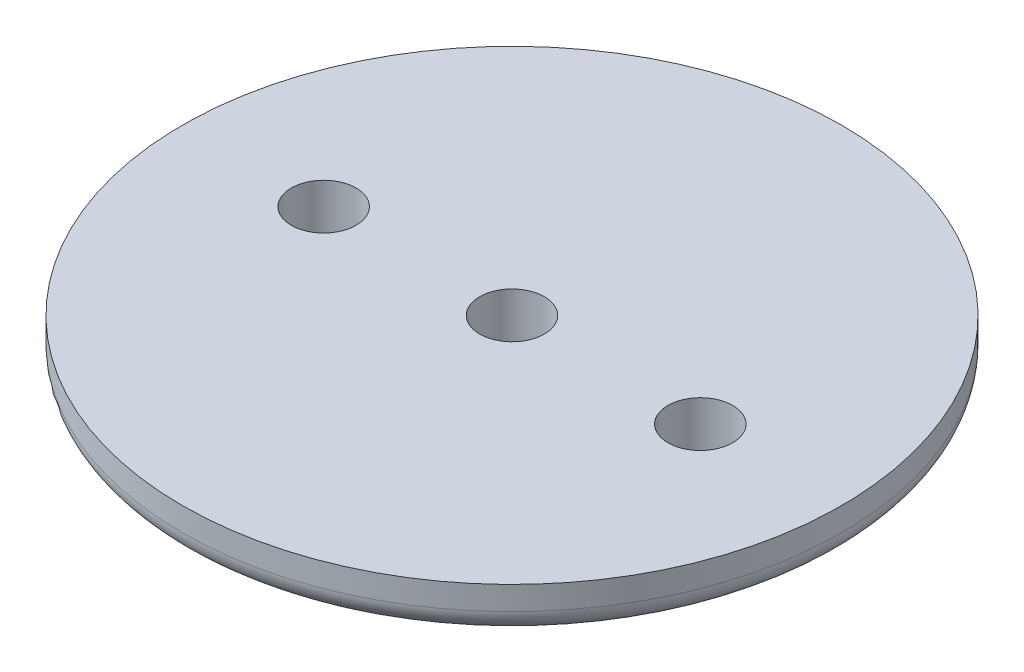
SolidWorks part; units mm, degrees
ref_plane "Front Plane" through (0, 0, 0) normal (0, 0, 1) x (1, 0, 0)
ref_plane "Top Plane" through (0, 0, 0) normal (0, 1, 0) x (1, 0, 0)
ref_plane "Right Plane" through (0, 0, 0) normal (1, 0, 0) x (0, 0, -1)
sketch "Sketch1" plane through (0, 0, 0) normal (0, 0, 1) x (1, 0, 0)
  line L1 (0, 0) -> (20.6375, 0)
  line L2 (0, 0) -> (0, 3.175)
  line L3 (0, 3.175) -> (22.225, 3.175)
  line L4 (22.225, 1.5875) -> (22.225, 3.175)
  arc A0 (20.6375, 0) -> (22.225, 1.5875) centre (20.6375, 1.5875) ccw
  dimension "D3" = 1.5875
  dimension "D1" = 22.225
  dimension "D2" = 3.175
revolve "Revolve1" add sketch "Sketch1" angle 360 about L2
sketch "Sketch2" plane through (0, 3.175, 0) normal (0, 1, 0) x (1, 0, 0)
  circle A0 centre (0, 0) radius 2.1828
  circle A1 centre (12.7, 0) radius 2.1828
  circle A2 centre (-12.7, 0) radius 2.1828
  dimension "D1" = 4.3656
  dimension "D2" = 4.3656
  dimension "D3" = 4.3656
  dimension "D7" = 12.7
  dimension "D9" = 12.7
extrude "Cut-Extrude1" cut sketch "Sketch2" against normal through all both and the other way through all
